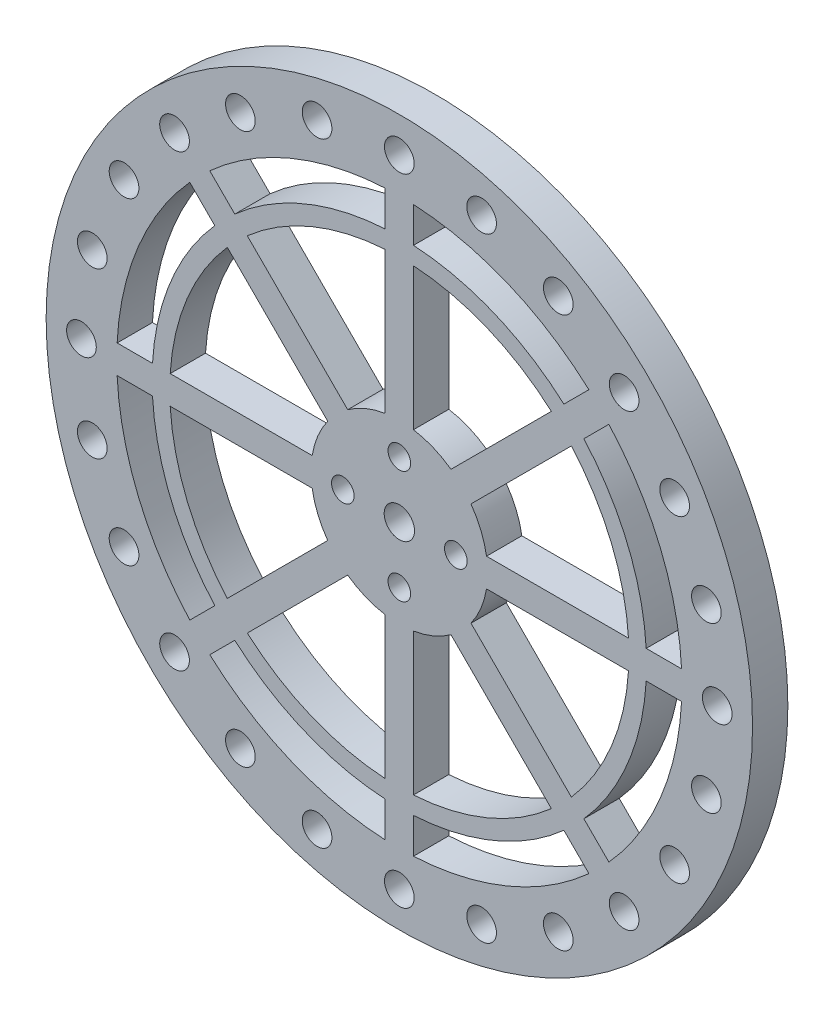
SolidWorks part; units mm, degrees
ref_plane "정면" through (0, 0, 0) normal (0, 0, 1) x (1, 0, 0)
ref_plane "윗면" through (0, 0, 0) normal (0, 1, 0) x (1, 0, 0)
ref_plane "우측면" through (0, 0, 0) normal (1, 0, 0) x (0, 0, -1)
sketch "Sketch1" plane through (0, 0, 0) normal (0, 0, 1) x (1, 0, 0)
  line L0 (-2, 39.95) -> (-2, 12.339)
  line L1 (2, 39.95) -> (2, 12.339)
  line L2 (0, 40) -> (0, 0) construction
  line L3 (26.8347, 29.6631) -> (7.3108, 10.1392)
  line L4 (29.6631, 26.8347) -> (10.1392, 7.3108)
  line L5 (39.95, 2) -> (12.339, 2)
  line L6 (39.95, -2) -> (12.339, -2)
  line L7 (29.6631, -26.8347) -> (10.1392, -7.3108)
  line L8 (26.8347, -29.6631) -> (7.3108, -10.1392)
  line L9 (2, -39.95) -> (2, -12.339)
  line L10 (-2, -39.95) -> (-2, -12.339)
  line L11 (-26.8347, -29.6631) -> (-7.3108, -10.1392)
  line L12 (-29.6631, -26.8347) -> (-10.1392, -7.3108)
  line L13 (-39.95, -2) -> (-12.339, -2)
  line L14 (-39.95, 2) -> (-12.339, 2)
  line L15 (-29.6631, 26.8347) -> (-10.1392, 7.3108)
  line L16 (-26.8347, 29.6631) -> (-7.3108, 10.1392)
  circle A0 centre (0, 0) radius 50
  circle A1 centre (0, 0) radius 40
  circle A2 centre (0, 0) radius 35
  circle A3 centre (0, 0) radius 32.5
  circle A4 centre (0, 0) radius 12.5
  point P28 (0, 0)
  dimension "D1" = 100
  dimension "D3" = 70
  dimension "D4" = 65
  dimension "D5" = 25
  dimension "D6" = 4
  dimension "D7" = 2
  dimension "D2" = 10
  dimension "D8" = 8
extrude "Extrude2" add sketch "Sketch1" along normal mid plane 5
sketch "Sketch2" plane through (0, 0, 2.5) normal (0, 0, 1) x (1, 0, 0)
  circle A0 centre (0, 45) radius 2.1
  circle A1 centre (11.6469, 43.4667) radius 2.1
  circle A2 centre (22.5, 38.9711) radius 2.1
  circle A3 centre (31.8198, 31.8198) radius 2.1
  circle A4 centre (38.9711, 22.5) radius 2.1
  circle A5 centre (43.4667, 11.6469) radius 2.1
  circle A6 centre (45, 0) radius 2.1
  circle A7 centre (43.4667, -11.6469) radius 2.1
  circle A8 centre (38.9711, -22.5) radius 2.1
  circle A9 centre (31.8198, -31.8198) radius 2.1
  circle A10 centre (22.5, -38.9711) radius 2.1
  circle A11 centre (11.6469, -43.4667) radius 2.1
  circle A12 centre (0, -45) radius 2.1
  circle A13 centre (-11.6469, -43.4667) radius 2.1
  circle A14 centre (-22.5, -38.9711) radius 2.1
  circle A15 centre (-31.8198, -31.8198) radius 2.1
  circle A16 centre (-38.9711, -22.5) radius 2.1
  circle A17 centre (-43.4667, -11.6469) radius 2.1
  circle A18 centre (-45, 0) radius 2.1
  circle A19 centre (-43.4667, 11.6469) radius 2.1
  circle A20 centre (-38.9711, 22.5) radius 2.1
  circle A21 centre (-31.8198, 31.8198) radius 2.1
  circle A22 centre (-22.5, 38.9711) radius 2.1
  circle A23 centre (-11.6469, 43.4667) radius 2.1
  point P43 (0, 0)
  dimension "D2" = 4.2
  dimension "D1" = 45
  dimension "D3" = 24
extrude "Extrude3" cut sketch "Sketch2" against normal through all both and the other way through all
sketch "Sketch3" plane through (0, 0, 2.5) normal (0, 0, 1) x (1, 0, 0)
  circle A1 centre (0, 8) radius 1.6
  circle A2 centre (0, 0) radius 2.15
  circle A3 centre (8, 0) radius 1.6
  circle A4 centre (0, -8) radius 1.6
  circle A5 centre (-8, 0) radius 1.6
  point P2 (0, 0)
  point P7 (0, 0)
  point P8 (-9.4369, -0.3961)
  point P15 (0, 0)
  point P16 (0, 0)
  dimension "D1" = 3.2
  dimension "D3" = 4.3
  dimension "D2" = 8
  dimension "D4" = 4
extrude "Extrude4" cut sketch "Sketch3" against normal up to next
